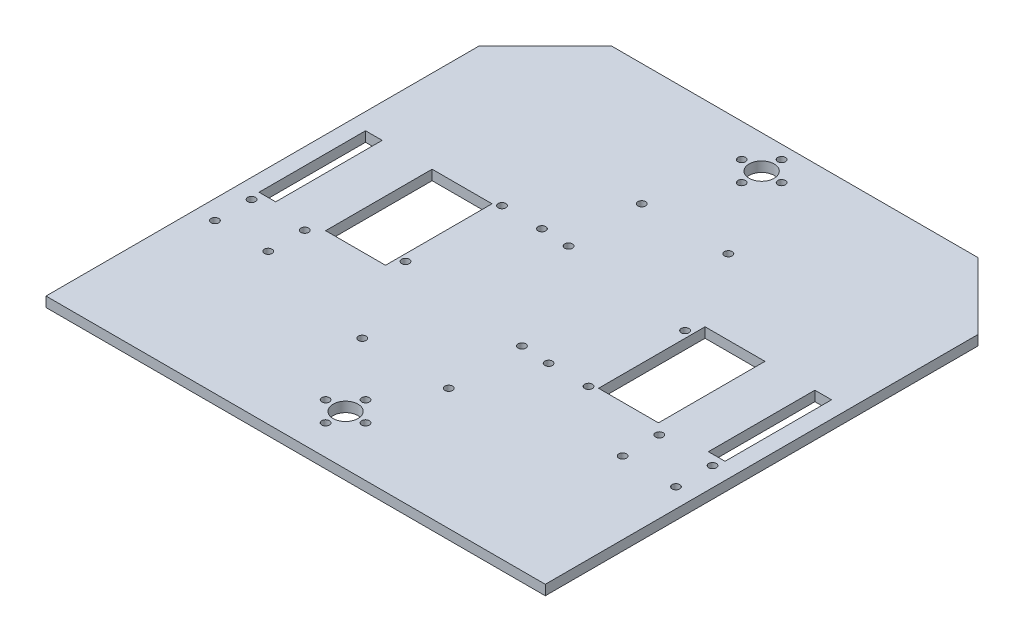
SolidWorks part; units mm, degrees
ref_plane "Plan de face" through (0, 0, 0) normal (0, 0, 1) x (1, 0, 0)
ref_plane "Plan de dessus" through (0, 0, 0) normal (0, 1, 0) x (1, 0, 0)
ref_plane "Plan de droite" through (0, 0, 0) normal (1, 0, 0) x (0, 0, -1)
sketch "Esquisse1" plane through (0, 0, 0) normal (0, 1, 0) x (1, 0, 0)
  line L0 (-150, 0) -> (-150, 260)
  line L2 (150, 0) -> (150, 260)
  line L3 (-150, 260) -> (-110, 260) construction
  line L4 (-110, 260) -> (-110, 300) construction
  line L5 (150, 260) -> (110, 260) construction
  line L6 (110, 260) -> (110, 300) construction
  line L8 (-150, 260) -> (-110, 300)
  line L9 (-110, 300) -> (110, 300)
  line L11 (110, 300) -> (150, 260)
  line L12 (-150, 0) -> (-120, 0) construction
  line L14 (150, 0) -> (120, 0) construction
  line L17 (-150, 260) -> (-120, 260) construction
  line L19 (150, 260) -> (120, 260) construction
  line L25 (-150, 0) -> (150, 0) construction
  line L28 (-150, 0) -> (150, 0)
  line L31 (0, 30) -> (0, 18) construction
  line L32 (150, 150) -> (-150, 150) construction
  line L37 (0, 30) -> (12, 30) construction
  line L38 (0, 30) -> (-12, 30) construction
  line L39 (0, 30) -> (0, 42) construction
  line L40 (0, 0) -> (0, 18) construction
  line L41 (0, 280) -> (12, 280) construction
  line L42 (0, 300) -> (0, 280) construction
  line L43 (12, 280) -> (0, 280) construction
  line L44 (0, 280) -> (0, 268) construction
  line L45 (0, 268) -> (0, 280) construction
  line L46 (0, 280) -> (-12, 280) construction
  line L47 (-12, 280) -> (0, 280) construction
  line L48 (0, 280) -> (0, 292) construction
  line L49 (0, 300) -> (0, 0) construction
  circle A21 centre (0, 30) radius 7.5
  circle A22 centre (0, 18) radius 2.3
  circle A23 centre (12, 30) radius 2.3
  circle A24 centre (0, 42) radius 2.3
  circle A25 centre (-12, 30) radius 2.3
  circle A26 centre (0, 280) radius 7.5
  circle A27 centre (-12, 280) radius 2.3
  circle A28 centre (0, 268) radius 2.3
  circle A29 centre (12, 280) radius 2.3
  circle A30 centre (0, 292) radius 2.3
  point P15 (0, 0)
extrude "Boss.-Extru.1" add sketch "Esquisse1" along normal blind 6
sketch "Esquisse7" plane through (0, 6, 0) normal (0, 1, 0) x (1, 0, 0)
  line L0 (-130, 150) -> (0, 150)
  line L2 (150, 150) -> (-150, 150) construction
  line L4 (-130, 182) -> (-140, 182)
  line L5 (-140, 182) -> (-140, 118)
  line L6 (-140, 118) -> (-130, 118)
  line L8 (-130, 182) -> (-130, 118)
extrude "Enlèv. mat.-Extru.9" cut sketch "Esquisse7" against normal blind 10.5 contours L8 L4 L5 L6
sketch "Esquisse6" plane through (0, 6, 0) normal (0, 1, 0) x (1, 0, 0)
  line L0 (-142.5, 116) -> (-134.5, 116) construction
  line L2 (-142.5, 116) -> (-142.5, 150) construction
  line L3 (-142.5, 116) -> (-142.5, 108) construction
  line L11 (-142.5, 108) -> (-134.5, 108) construction
  line L12 (-134.5, 108) -> (-134.5, 116) construction
  line L14 (-142.5, 150) -> (-150, 150) construction
  line L15 (-142.5, 116) -> (-102.5, 116) construction
  line L16 (-102.5, 116) -> (-102.5, 108) construction
  line L17 (-102.5, 108) -> (-110.5, 108) construction
  line L18 (-110.5, 108) -> (-110.5, 116) construction
  line L19 (-110.5, 116) -> (-134.5, 116) construction
  line L20 (-134.5, 116) -> (-134.5, 86) construction
  line L21 (-134.5, 86) -> (-142.5, 86) construction
  line L22 (-142.5, 86) -> (-142.5, 94) construction
  line L23 (-142.5, 94) -> (-134.5, 94) construction
  line L24 (-134.5, 94) -> (-134.5, 86) construction
  line L25 (-134.5, 86) -> (-110.5, 86) construction
  line L26 (-110.5, 86) -> (-110.5, 94) construction
  line L27 (-110.5, 94) -> (-102.5, 94) construction
  line L28 (-102.5, 94) -> (-102.5, 86) construction
  line L29 (-102.5, 86) -> (-110.5, 86) construction
  line L30 (-102.5, 94) -> (-110.5, 86) construction
  line L31 (-110.5, 94) -> (-102.5, 86) construction
  line L32 (-142.5, 94) -> (-134.5, 86) construction
  line L33 (-142.5, 86) -> (-134.5, 94) construction
  line L34 (-142.5, 116) -> (-134.5, 108) construction
  line L35 (-142.5, 108) -> (-134.5, 116) construction
  line L71 (-110.5, 116) -> (-102.5, 108) construction
  line L72 (-110.5, 108) -> (-102.5, 116) construction
  line L73 (-110.5, 116) -> (-110.5, 86) construction
  circle A20 centre (-138.5, 90) radius 2.3
  circle A21 centre (-138.5, 112) radius 2.3
  circle A22 centre (-106.5, 112) radius 2.3
  circle A23 centre (-106.5, 90) radius 2.3
  dimension "D1" = 7.5
  dimension "D2" = 34
sketch "Esquisse4" plane through (0, 6, 0) normal (0, 1, 0) x (1, 0, 0)
  line L0 (-150, 150) -> (-100, 150) construction
  line L1 (-100, 150) -> (-100, 182)
  line L2 (-100, 182) -> (-64, 182)
  line L8 (150, 150) -> (-150, 150) construction
  line L16 (-100, 150) -> (-100, 118)
  line L17 (-100, 118) -> (-64, 118)
  line L18 (-64, 118) -> (-64, 182)
extrude "Enlèv. mat.-Extru.10" cut sketch "Esquisse6" against normal blind 50
extrude "Enlèv. mat.-Extru.11" cut sketch "Esquisse4" against normal blind 50
mirror "Symétrie1" about plane through (0, 0, 0) normal (1, 0, 0) of "Enlèv. mat.-Extru.9"
mirror "Symétrie2" about plane through (0, 0, 0) normal (1, 0, 0) of "Enlèv. mat.-Extru.11"
mirror "Symétrie3" about plane through (0, 0, 0) normal (1, 0, 0) of "Enlèv. mat.-Extru.10"
sketch "Esquisse11" plane through (0, 6, 0) normal (0, 1, 0) x (1, 0, 0)
  line L0 (-64, 150) -> (-64, 130) construction
  line L2 (-64, 118) -> (-64, 182) construction
  line L3 (32, 223) -> (-23, 223) construction
  line L4 (-23, 223) -> (-23, 187) construction
  line L5 (-23, 187) -> (-15, 187) construction
  line L6 (-15, 187) -> (-15, 179) construction
  line L7 (-64, 150) -> (-64, 180) construction
  line L8 (-64, 180) -> (-32, 180) construction
  line L9 (-32, 180) -> (-32, 77) construction
  line L10 (-64, 130) -> (-56, 130) construction
  line L11 (-56, 130) -> (-56, 122) construction
  line L12 (-56, 122) -> (-64, 130) construction
  line L13 (-64, 130) -> (-56, 130) construction
  line L14 (-56, 130) -> (-64, 122) construction
  line L15 (-64, 122) -> (-56, 122) construction
  line L16 (-64, 180) -> (-64, 188) construction
  line L17 (-64, 188) -> (-56, 188) construction
  line L18 (-56, 188) -> (-56, 180) construction
  line L19 (-56, 180) -> (-64, 188) construction
  line L20 (-64, 188) -> (-56, 188) construction
  line L21 (64, 150) -> (64, 170) construction
  line L22 (64, 170) -> (56, 170) construction
  line L23 (56, 170) -> (56, 178) construction
  line L24 (56, 178) -> (64, 178) construction
  line L25 (64, 178) -> (64, 170) construction
  line L26 (64, 170) -> (56, 178) construction
  line L27 (56, 178) -> (56, 170) construction
  line L28 (56, 170) -> (64, 178) construction
  line L29 (64, 150) -> (64, 120) construction
  line L30 (64, 118) -> (64, 182) construction
  line L31 (64, 120) -> (32, 120) construction
  line L32 (32, 120) -> (32, 165) construction
  line L33 (32, 165) -> (37, 165) construction
  line L34 (37, 165) -> (37, 129.3158) construction
  line L35 (37, 129.3158) -> (64, 129.3158) construction
  line L36 (32, 120) -> (32, 223) construction
  line L37 (-15, 179) -> (-23, 179) construction
  line L38 (-23, 179) -> (-23, 187) construction
  line L39 (-23, 187) -> (-15, 179) construction
  line L40 (-15, 179) -> (-15, 187) construction
  line L41 (-15, 187) -> (-23, 179) construction
  line L42 (32, 223) -> (37, 223) construction
  line L43 (37, 223) -> (37, 231) construction
  line L44 (37, 231) -> (29, 231) construction
  line L45 (-23, 223) -> (-23, 231) construction
  line L46 (-23, 231) -> (-15, 231) construction
  line L47 (64, 120) -> (64, 112) construction
  line L48 (64, 112) -> (56, 112) construction
  line L49 (56, 112) -> (56, 120) construction
  line L50 (56, 120) -> (64, 112) construction
  line L51 (64, 112) -> (64, 120) construction
  line L52 (64, 120) -> (56, 112) construction
  line L53 (56, 112) -> (56, 120) construction
  line L54 (56, 120) -> (32, 120) construction
  line L55 (32, 120) -> (32, 112) construction
  line L56 (32, 112) -> (40, 112) construction
  line L57 (40, 112) -> (40, 120) construction
  line L58 (40, 120) -> (32, 112) construction
  line L59 (32, 112) -> (32, 120) construction
  line L60 (32, 120) -> (40, 112) construction
  line L61 (-15, 231) -> (-15, 223) construction
  line L62 (-15, 223) -> (-23, 231) construction
  line L63 (-23, 231) -> (-23, 223) construction
  line L64 (-23, 223) -> (-15, 231) construction
  line L65 (29, 231) -> (29, 223) construction
  line L66 (29, 223) -> (37, 231) construction
  line L67 (37, 231) -> (29, 231) construction
  line L68 (29, 231) -> (37, 223) construction
  line L69 (-56, 188) -> (-64, 180) construction
  line L70 (-64, 180) -> (-32, 180) construction
  line L71 (-32, 180) -> (-32, 188) construction
  line L72 (-32, 188) -> (-40, 188) construction
  line L73 (-40, 188) -> (-40, 180) construction
  line L74 (-40, 180) -> (-32, 188) construction
  line L75 (-32, 188) -> (-40, 188) construction
  line L76 (-40, 188) -> (-32, 180) construction
  line L77 (-32, 180) -> (-32, 77) construction
  line L78 (-32, 77) -> (-37, 77) construction
  line L79 (-37, 77) -> (-37, 69) construction
  line L80 (-37, 69) -> (-29, 69) construction
  line L81 (-29, 69) -> (-29, 77) construction
  line L82 (-29, 77) -> (-37, 69) construction
  line L83 (-37, 69) -> (-37, 77) construction
  line L84 (-37, 77) -> (-29, 69) construction
  line L85 (-29, 69) -> (-29, 77) construction
  line L86 (-29, 77) -> (-37, 77) construction
  line L87 (-37, 77) -> (23, 77) construction
  line L88 (23, 77) -> (23, 69) construction
  line L89 (23, 69) -> (15, 69) construction
  line L90 (15, 69) -> (15, 77) construction
  line L91 (15, 77) -> (23, 69) construction
  line L92 (23, 69) -> (23, 77) construction
  line L93 (23, 77) -> (15, 69) construction
  line L94 (15, 69) -> (23, 69) construction
  line L95 (23, 69) -> (23, 77) construction
  line L96 (23, 77) -> (23, 113) construction
  line L97 (23, 113) -> (-32, 113) construction
  line L98 (23, 113) -> (23, 121) construction
  line L99 (23, 121) -> (15, 121) construction
  line L100 (15, 121) -> (15, 113) construction
  line L101 (15, 113) -> (23, 121) construction
  line L102 (23, 121) -> (15, 121) construction
  line L103 (15, 121) -> (23, 113) construction
  circle A4 centre (36, 116) radius 2.3
  circle A5 centre (60, 116) radius 2.3
  circle A7 centre (60, 174) radius 2.3
  circle A8 centre (-19, 227) radius 2.3
  circle A12 centre (-19, 183) radius 2.3
  circle A13 centre (33, 227) radius 2.3
  circle A14 centre (19, 117) radius 2.3
  circle A15 centre (19, 73) radius 2.3
  circle A17 centre (-33, 73) radius 2.3
  circle A18 centre (-60, 126) radius 2.3
  circle A19 centre (-36, 184) radius 2.3
  circle A20 centre (-60, 184) radius 2.3
  dimension "D1" = 50
  dimension "D2" = 32
  dimension "D3" = 20
extrude "Enlèv. mat.-Extru.15" cut sketch "Esquisse11" against normal blind 10
